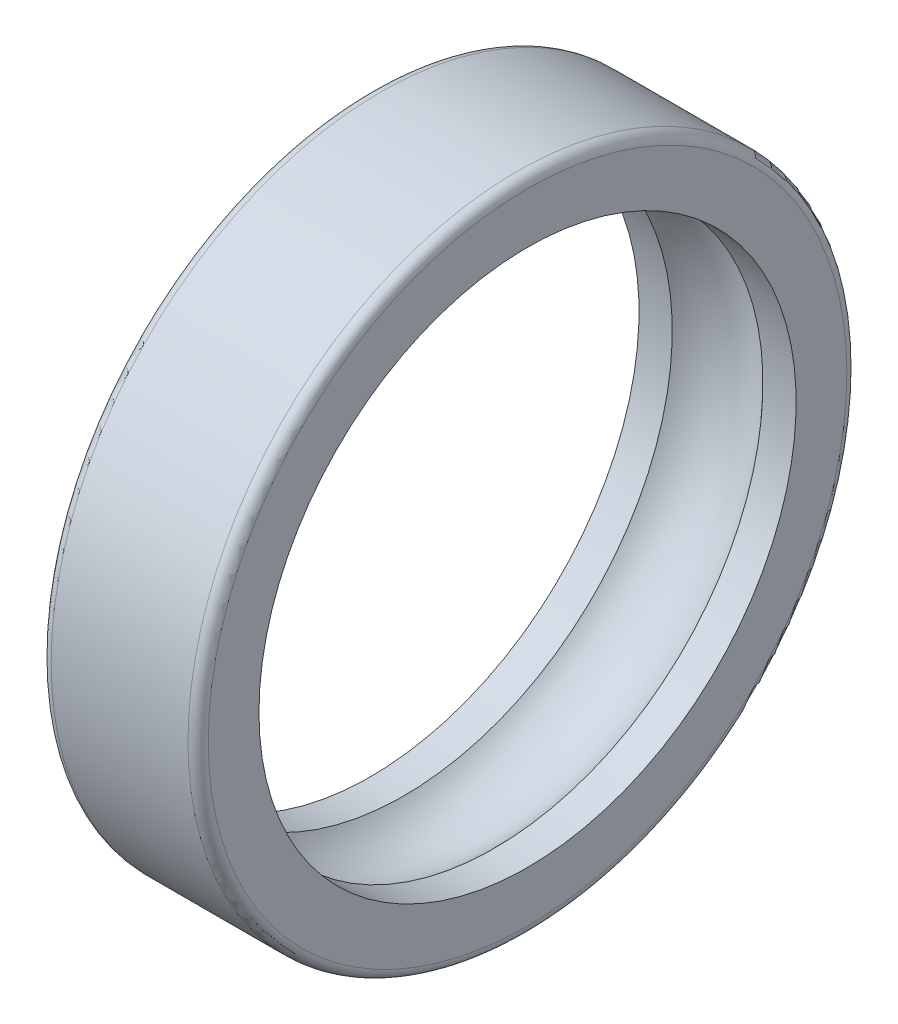
SolidWorks part; units mm, degrees
ref_plane "前基準面" through (0, 0, 0) normal (0, 0, 1) x (1, 0, 0)
ref_plane "上基準面" through (0, 0, 0) normal (0, 1, 0) x (1, 0, 0)
ref_plane "右基準面" through (0, 0, 0) normal (1, 0, 0) x (0, 0, -1)
sketch "草圖1" plane through (0, 0, 0) normal (0, 0, 1) x (1, 0, 0)
  line L0 (0, 0) -> (88.835, 0) construction
  line L6 (4.389, 53) -> (4.389, 45) construction
  line L7 (-11.111, 65) -> (19.889, 65)
  line L8 (-11.111, 65) -> (-11.111, 53)
  line L9 (-11.111, 53) -> (-4.5552, 53)
  line L10 (19.889, 65) -> (19.889, 53)
  line L11 (13.3333, 53) -> (19.889, 53)
  arc A1 (13.3333, 53) -> (-4.5552, 53) centre (4.389, 45) ccw
  point P2 (0, 0)
  point P9 (4.389, 45)
  dimension "D5" = 24
  dimension "D1" = 65
  dimension "D2" = 31
  dimension "D3" = 53
  dimension "D4" = 8
revolve "旋轉1" add sketch "草圖1" angle 360 about L0
fillet "圓角1" radius 2 2 edges at (19.889, 0, 65) (-11.111, 0, 65)
